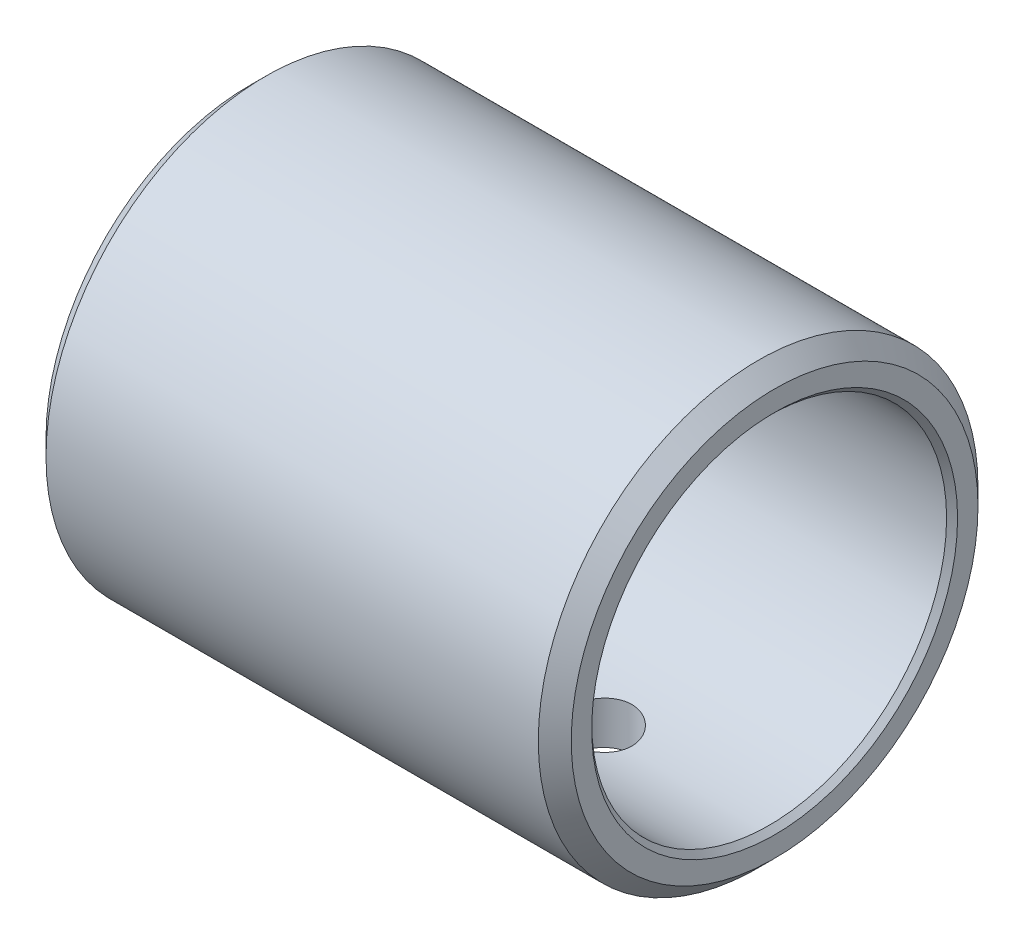
SolidWorks part; units mm, degrees
material "OVAKO 280 HB"
ref_plane "Front Plane" through (0, 0, 0) normal (0, 0, 1) x (1, 0, 0)
ref_plane "Top Plane" through (0, 0, 0) normal (0, 1, 0) x (1, 0, 0)
ref_plane "Right Plane" through (0, 0, 0) normal (1, 0, 0) x (0, 0, -1)
sketch "Sketch2" plane through (0, 0, 0) normal (0, 0, 1) x (1, 0, 0)
  line L0 (0, 16.15) -> (0, 20.0075)
  line L1 (0, 20.0075) -> (-47.8, 20.0075)
  line L2 (-47.8, 20.0075) -> (-47.8, 16.15)
  line L3 (-47.8, 16.15) -> (0, 16.15)
  line L4 (0, 0) -> (-47.8, 0) construction
  dimension "D1" = 47.8
  dimension "D2" = 32.3
  dimension "D3" = 40.015
revolve "Revolve1" add sketch "Sketch2" angle 360 about L4
chamfer "Chamfer1" distance 1.5 angle 45 2 edges at (0, 0, -20.0075) (-47.8, 0, -20.0075)
chamfer "Chamfer2" distance 0.5 angle 45 2 edges at (0, 0, -16.15) (-47.8, 0, -16.15)
sketch "Sketch3" plane through (0, 0, 0) normal (0, 1, 0) x (1, 0, 0)
  line L0 (0, -18.5075) -> (0, 18.5075) construction
  circle A0 centre (-16, 0) radius 3
  circle A1 centre (-32, 0) radius 3
  dimension "D3" = 6
  dimension "D1" = 16
  dimension "D2" = 32
extrude "Cut-Extrude1" cut sketch "Sketch3" against normal through all
sketch "Sketch4" plane through (0, 0, 0) normal (0, 0, 1) x (1, 0, 0)
  line L0 (-47.95, 18.3575) -> (-47.95, 16.8)
  line L1 (-46.1825, 20.125) -> (-1.6175, 20.125)
  line L2 (0.15, 18.3575) -> (0.15, 16.8)
  line L3 (-0.5, 16.15) -> (-47.3, 16.15)
  line L4 (0, 16.15) -> (0, 20.0075) construction
  line L6 (0, 0) -> (8.8713, 0) construction
  line L7 (0, 18.5075) -> (-1.5, 20.0075) construction
  line L8 (0.15, 18.3575) -> (-1.6175, 20.125)
  line L9 (-46.3, 20.0075) -> (-47.8, 18.5075) construction
  line L10 (-46.1825, 20.125) -> (-47.95, 18.3575)
  line L11 (-47.3, 16.15) -> (-47.95, 16.8)
  line L12 (-47.3, 16.15) -> (-47.8, 16.65) construction
  line L13 (-0.5, 16.15) -> (0.15, 16.8)
  dimension "D1" = 0.15
  dimension "D2" = 48.1
  dimension "D3" = 32.3
  dimension "D4" = 40.25
  dimension "D5" = 45
  dimension "D6" = 45
  dimension "D7" = 0.65
revolve "Revolve2" [suppressed] add sketch "Sketch4" angle 360 about L6
